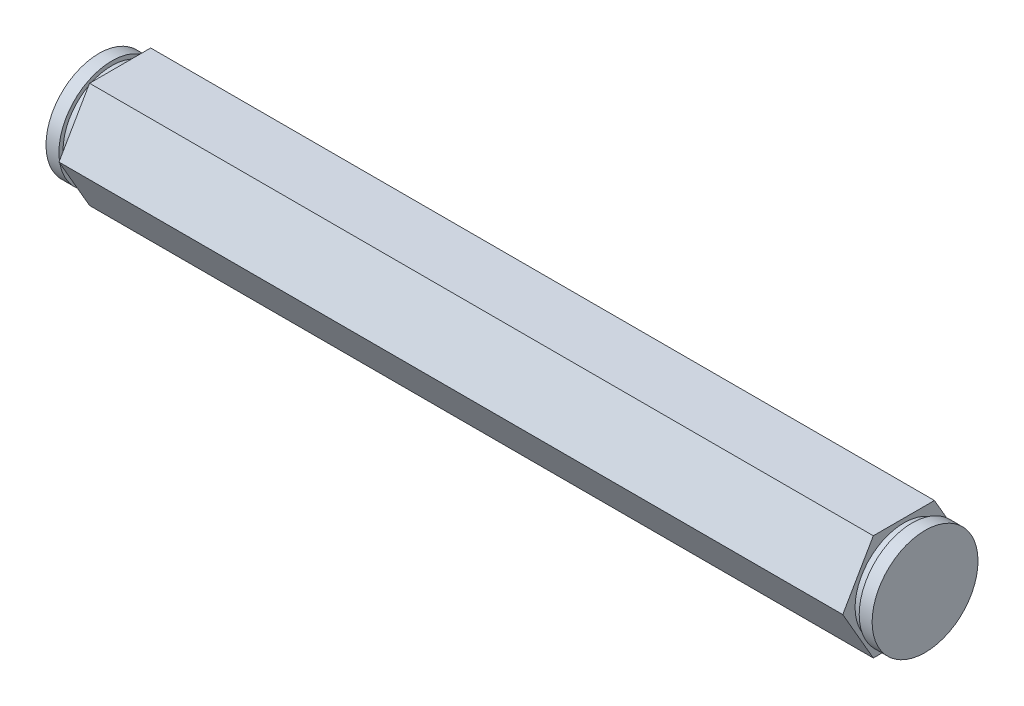
SolidWorks part; units mm, degrees
material "7075-T6 (SN)"
ref_plane "Front Plane" through (0, 0, 0) normal (0, 0, 1) x (1, 0, 0)
ref_plane "Top Plane" through (0, 0, 0) normal (0, 1, 0) x (1, 0, 0)
ref_plane "Right Plane" through (0, 0, 0) normal (1, 0, 0) x (0, 0, -1)
sketch "Sketch1" plane through (0, 0, 0) normal (1, 0, 0) x (0, 0, -1)
  line L1 (7.3323, 0) -> (3.6662, 6.35)
  line L2 (3.6662, 6.35) -> (-3.6662, 6.35)
  line L3 (-3.6662, 6.35) -> (-7.3323, 0)
  line L4 (-7.3323, 0) -> (-3.6662, -6.35)
  line L5 (-3.6662, -6.35) -> (3.6662, -6.35)
  line L6 (3.6662, -6.35) -> (7.3323, 0)
  circle A0 centre (0, 0) radius 6.35 construction
  dimension "D1" = 12.7
extrude "Boss-Extrude1" add sketch "Sketch1" along normal mid plane 99.0885
sketch "Sketch2" plane through (0, 0, 0) normal (0, 1, 0) x (1, 0, 0)
  line L0 (47.0043, -5.8547) -> (47.9949, -5.8547)
  line L1 (47.9949, -5.8547) -> (47.9949, -6.35)
  line L2 (47.9949, -6.35) -> (49.5443, -6.35)
  line L3 (49.5443, -6.35) -> (49.5443, -8.89)
  line L4 (49.5443, -8.89) -> (47.0043, -8.89)
  line L5 (47.0043, -8.89) -> (47.0043, -5.8547)
  line L6 (0, 0) -> (49.5443, 0) construction
  dimension "D1" = 2.54
  dimension "D2" = 6.35
  dimension "D3" = 5.8547
  dimension "D4" = 2.54
  dimension "D5" = 0.9906
revolve "Cut-Revolve1" cut sketch "Sketch2" angle 360 about L6
mirror "Mirror1" about plane through (0, 0, 0) normal (1, 0, 0) of "Cut-Revolve1"
